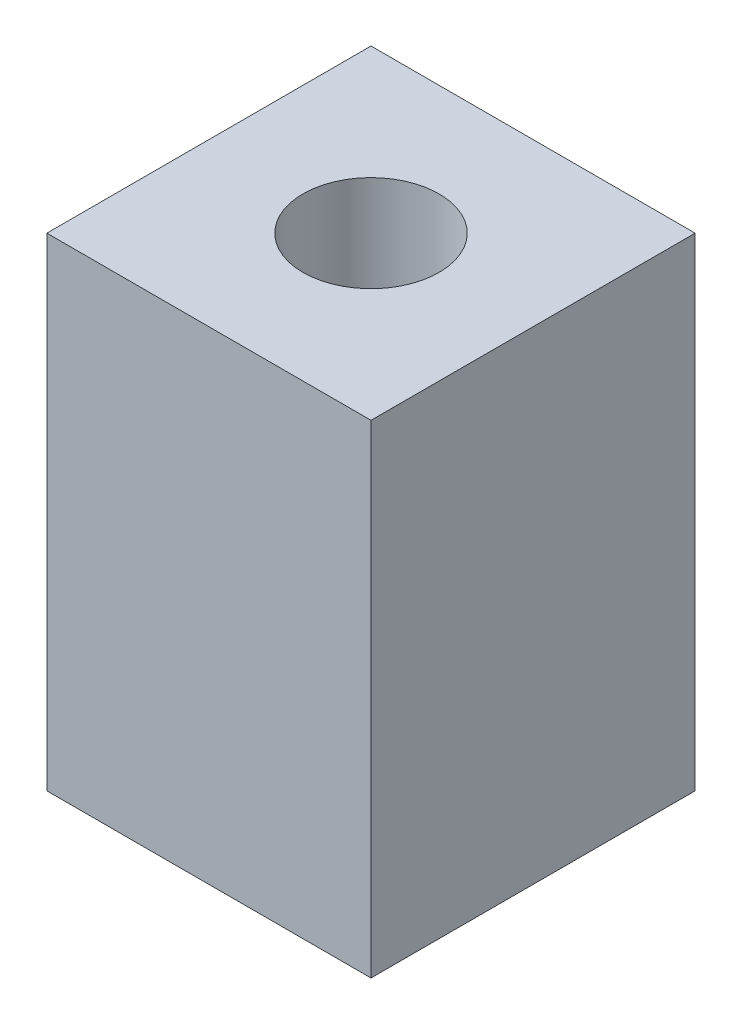
SolidWorks part; units mm, degrees
ref_plane "Спереди" through (0, 0, 0) normal (0, 0, 1) x (1, 0, 0)
ref_plane "Сверху" through (0, 0, 0) normal (0, 1, 0) x (1, 0, 0)
ref_plane "Справа" through (0, 0, 0) normal (1, 0, 0) x (0, 0, -1)
sketch "Эскиз1" plane through (0, 0, 0) normal (0, 1, 0) x (1, 0, 0)
  line L0 (-5, 5) -> (5, 5)
  line L1 (5, 5) -> (5, -5)
  line L2 (5, -5) -> (-5, -5)
  line L3 (-5, -5) -> (-5, 5)
  circle A0 centre (0, 0) radius 2.1
extrude "Бобышка-Вытянуть1" add sketch "Эскиз1" along normal blind 14.9
